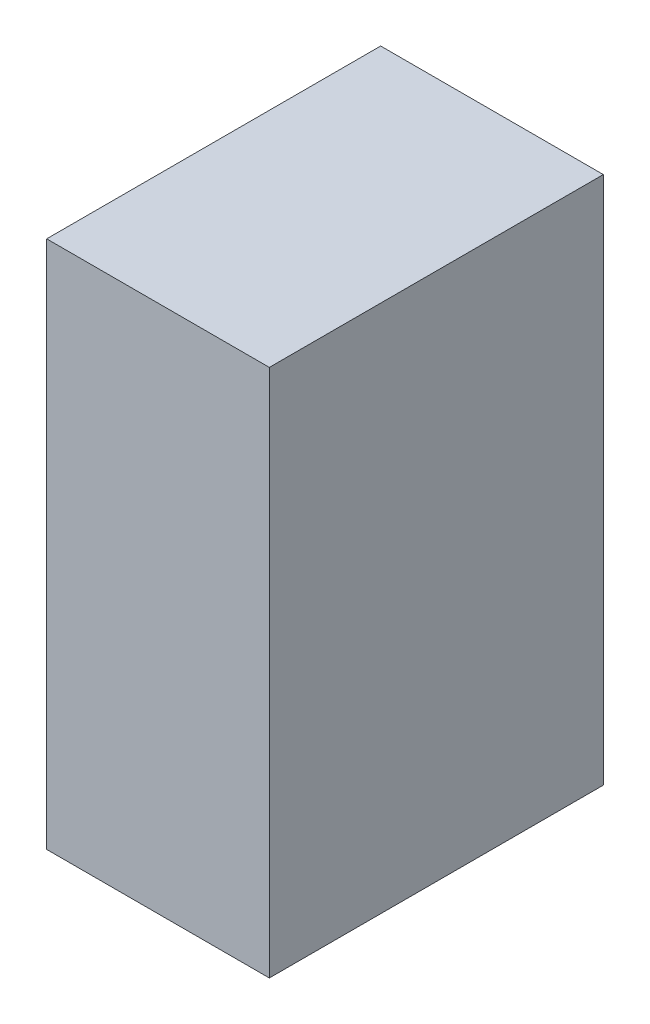
SolidWorks part; units mm, degrees
ref_plane "Plan de face" through (0, 0, 0) normal (0, 0, 1) x (1, 0, 0)
ref_plane "Plan de dessus" through (0, 0, 0) normal (0, 1, 0) x (1, 0, 0)
ref_plane "Plan de droite" through (0, 0, 0) normal (1, 0, 0) x (0, 0, -1)
sketch "Esquisse1" plane through (0, 0, 0) normal (0, 1, 0) x (1, 0, 0)
  line L1 (4, -6) -> (-4, -6)
  line L2 (4, -6) -> (4, 6)
  line L3 (4, 6) -> (-4, 6)
  line L4 (-4, -6) -> (-4, 6)
  line L5 (4, -6) -> (-4, 6) construction
  line L6 (4, 6) -> (-4, -6) construction
  point P0 (0, 0)
  dimension "D1" = 8
  dimension "D2" = 12
extrude "Boss.-Extru.1" add sketch "Esquisse1" along normal blind 19
